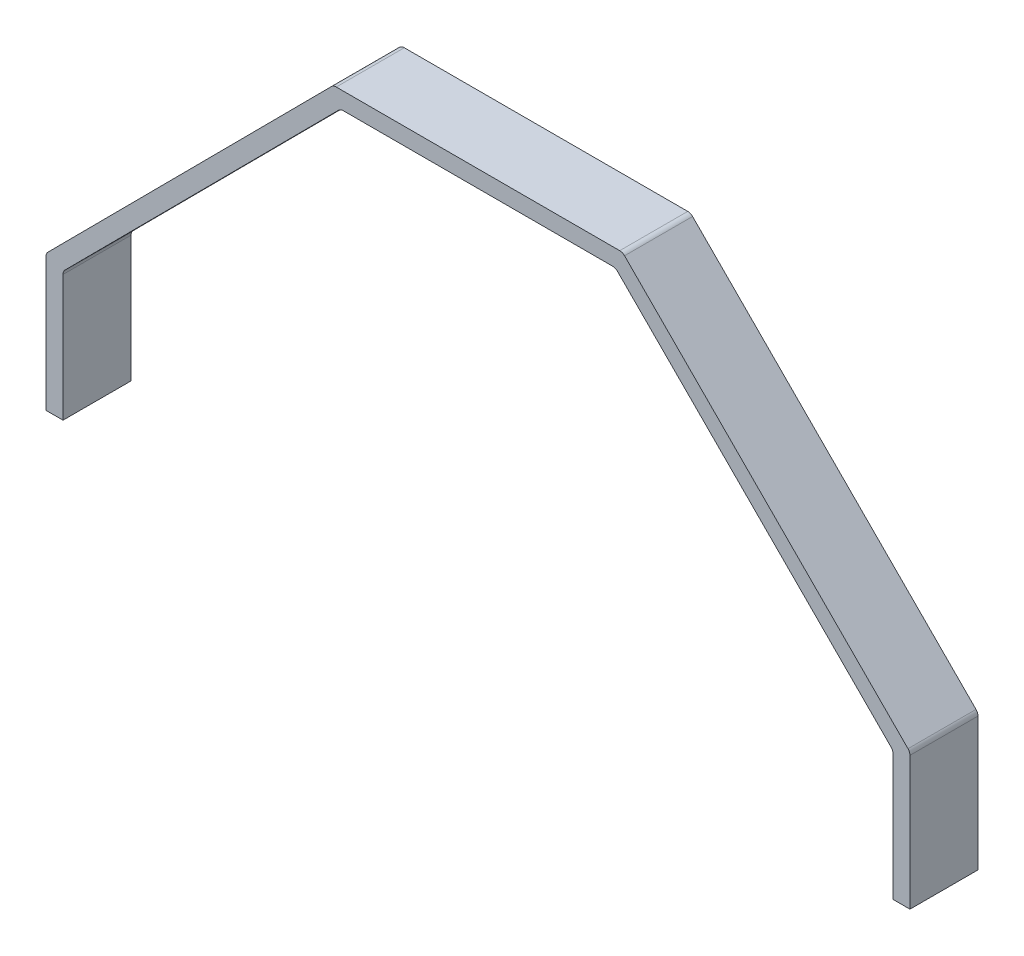
SolidWorks part; units mm, degrees
ref_plane "Front Plane" through (0, 0, 0) normal (0, 0, 1) x (1, 0, 0)
ref_plane "Top Plane" through (0, 0, 0) normal (0, 1, 0) x (1, 0, 0)
ref_plane "Right Plane" through (0, 0, 0) normal (1, 0, 0) x (0, 0, -1)
sketch "Sketch1" plane through (0, 0, 0) normal (0, 0, 1) x (1, 0, 0)
  line L0 (42.5, 0) -> (-42.5, 0)
  line L1 (42.5, 0) -> (127, -85)
  line L2 (127, -85) -> (127, -125)
  line L3 (-42.5, 0) -> (-127, -85)
  line L4 (-127, -85) -> (-127, -125)
  line L5 (122, -87.0624) -> (122, -125)
  line L6 (40.4203, -5) -> (122, -87.0624)
  line L7 (40.4203, -5) -> (-40.4203, -5)
  line L8 (-40.4203, -5) -> (-122, -87.0624)
  line L9 (-122, -87.0624) -> (-122, -125)
  line L10 (-127, -125) -> (-122, -125)
  line L11 (122, -125) -> (127, -125)
  point P4 (0, 0)
  dimension "D1" = 85
  dimension "D2" = 254
  dimension "D3" = 125
  dimension "D4" = 127
  dimension "D5" = 40
  dimension "D6" = 5
extrude "Boss-Extrude1" add sketch "Sketch1" along normal blind 20
fillet "Fillet1" radius 2 8 edges at (122, -87.0624, 10) (40.4203, -5, 10) (-40.4203, -5, 10) (-122, -87.0624, 10) (-127, -85, 10) (127, -85, 10) (-42.5, 0, 10) (42.5, 0, 10)
